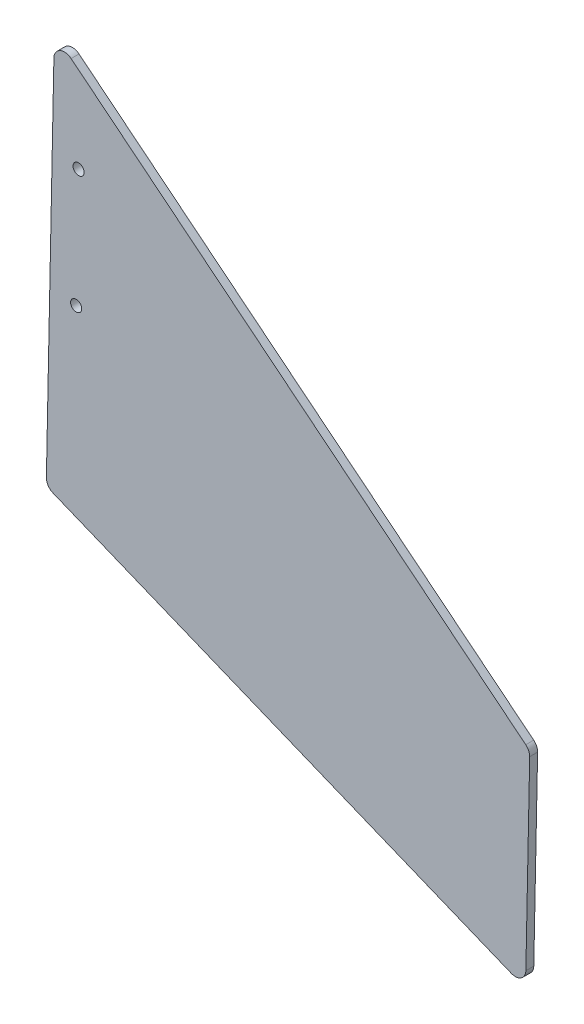
SolidWorks part; units mm, degrees
ref_plane "Спереди" through (0, 0, 0) normal (0, 0, 1) x (1, 0, 0)
ref_plane "Сверху" through (0, 0, 0) normal (0, 1, 0) x (1, 0, 0)
ref_plane "Справа" through (0, 0, 0) normal (1, 0, 0) x (0, 0, -1)
sketch "Эскиз1" plane through (0, 0, 0) normal (0, 0, 1) x (1, 0, 0)
  line L0 (0, 0) -> (-3.0687, -150)
  line L1 (-3.0687, -150) -> (178.4558, -224)
  line L2 (178.4558, -224) -> (180.0657, -145.3026)
  line L3 (180.0657, -145.3026) -> (0, 0)
  point P3 (0, 0)
  dimension "D1" = 150
  dimension "D2" = 224
  dimension "D3" = 183
  dimension "D4" = 183
extrude "Бобышка-Вытянуть1" add sketch "Эскиз1" along normal blind 3 contours L3 L0 L1 L2
fillet "Скругление1" radius 4 4 edges at (-3.0687, -150, 1.5) (0, 0, 1.5) (178.4558, -224, 1.5) (180.0657, -145.3026, 1.5)
sketch "Эскиз2" plane through (0, 0, 3) normal (0, 0, 1) x (1, 0, 0)
  line L0 (-0.1667, -8.1506) -> (-3.0124, -147.2518) construction
  circle A0 centre (9.1838, -40) radius 2.1
  circle A1 centre (8.2593, -85.1905) radius 2.1
  dimension "D1" = 4.2
  dimension "D4" = 4.2
  dimension "D2" = 10
  dimension "D3" = 45.2
  dimension "D5" = 10
  dimension "D6" = 40
extrude "Вырез-Вытянуть1" cut sketch "Эскиз2" against normal blind 3
